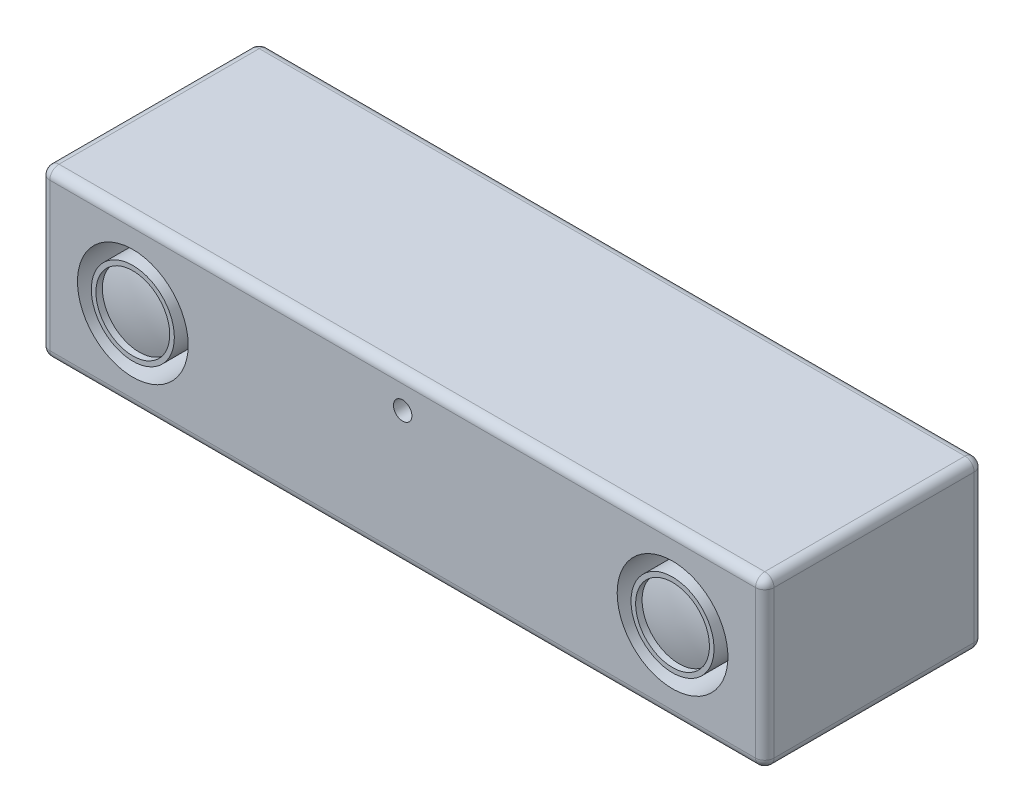
SolidWorks part; units mm, degrees
ref_plane "前视基准面" through (0, 0, 0) normal (0, 0, 1) x (1, 0, 0)
ref_plane "上视基准面" through (0, 0, 0) normal (0, 1, 0) x (1, 0, 0)
ref_plane "右视基准面" through (0, 0, 0) normal (1, 0, 0) x (0, 0, -1)
sketch "草图1" plane through (0, 0, 0) normal (0, 1, 0) x (1, 0, 0)
  line L0 (0, 0) -> (78.5, 0) construction
  line L1 (0, 0) -> (0, 23.7) construction
  line L2 (-78.5, 23.7) -> (78.5, 23.7)
  line L3 (78.5, 23.7) -> (78.5, -23.7)
  line L4 (-78.5, -23.7) -> (78.5, -23.7)
  line L5 (-78.5, 23.7) -> (-78.5, -23.7)
  point P9 (0, -23.7)
extrude "凸台-拉伸1" add sketch "草图1" along normal blind 36
fillet "圆角1" radius 2 12 edges at (-78.5, 18, -23.7) (0, 0, -23.7) (-78.5, 0, 0) (0, 0, 23.7) (78.5, 0, 0) (-78.5, 36, 0) (-78.5, 18, 23.7) (78.5, 18, 23.7) (78.5, 18, -23.7) (0, 36, -23.7) (78.5, 36, 0) (0, 36, 23.7)
sketch "草图2" plane through (0, 0, 23.7) normal (0, 0, 1) x (1, 0, 0)
  line L0 (0, 36) -> (0, 29) construction
  line L1 (-76.5, 36) -> (76.5, 36) construction
  line L2 (-78.5, 18) -> (-58.5, 18) construction
  line L3 (-78.5, 2) -> (-78.5, 34) construction
  circle A0 centre (0, 29) radius 2
  circle A1 centre (-58.5, 18) radius 12
  circle A2 centre (58.5, 18) radius 12
  circle A3 centre (-58.5, 18) radius 9
  circle A4 centre (58.5, 18) radius 9
extrude "切除-拉伸1" cut sketch "草图2" against normal blind 20
sketch "草图3" plane through (0, 0, 23.7) normal (0, 0, 1) x (1, 0, 0)
  line L0 (-58.5, 27) -> (-58.5, 9) construction
  circle A0 centre (-58.5, 18) radius 9 construction
ref_plane "基准面1" through (-58.5, 0, 0) normal (-1, 0, 0) x (0, -1, 0)
sketch "草图4" plane through (-58.5, 0, 0) normal (-1, 0, 0) x (0, -1, 0)
  line L0 (-18, 23.7) -> (-18, 23.4) construction
  line L1 (-27, 23.7) -> (-9, 23.7) construction
  line L2 (-18, 23.7) -> (-26, 23.7)
  line L5 (-18, 23.7) -> (-18, 23.4)
  line L6 (-18, 23.2309) -> (-18, -6.3) construction
  line L8 (-26, 23.7) -> (-26, 22.3023)
  arc A0 (-18, 23.4) -> (-26, 22.3023) centre (-18, -6.3) ccw
revolve "切除-旋转1" cut sketch "草图4" angle 360 about L6
mirror "镜向1" about plane through (0, 0, 0) normal (1, 0, 0) of "切除-旋转1"
